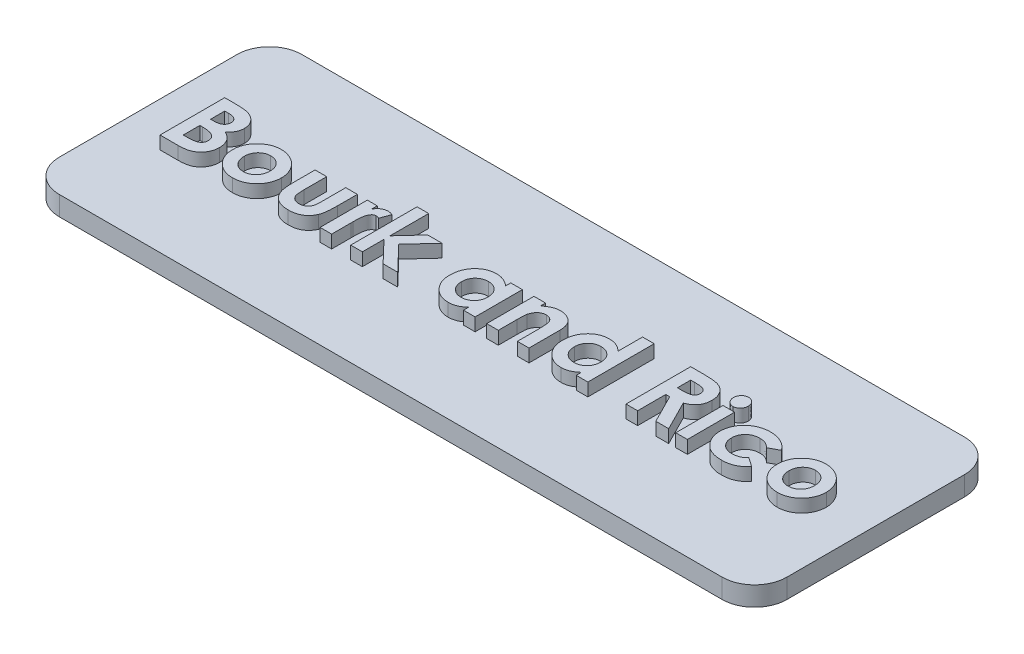
SolidWorks part; units mm, degrees
ref_plane "Front Plane" through (0, 0, 0) normal (0, 0, 1) x (1, 0, 0)
ref_plane "Top Plane" through (0, 0, 0) normal (0, 1, 0) x (1, 0, 0)
ref_plane "Right Plane" through (0, 0, 0) normal (1, 0, 0) x (0, 0, -1)
sketch "Sketch1" plane through (0, 0, 0) normal (0, 1, 0) x (1, 0, 0)
  line L1 (0, 7.5) -> (45, 7.5)
  line L2 (0, 7.5) -> (0, -7.5)
  line L3 (0, -7.5) -> (45, -7.5)
  line L4 (45, 7.5) -> (45, -7.5)
  line L5 (0, 7.5) -> (45, -7.5) construction
  line L6 (0, -7.5) -> (45, 7.5) construction
  dimension "D1" = 15
  dimension "D2" = 45
  dimension "D3" = 0
extrude "Boss-Extrude1" add sketch "Sketch1" along normal blind 1.2
sketch "Sketch2" plane through (0, 1.2, 0) normal (0, 1, 0) x (1, 0, 0)
  line L0 (0, -2) -> (45, -2) construction
  line L3 (0, -7.5) -> (45, -7.5) construction
  text T1 "<b>Bourk and Rico</b>" font "Century Gothic" height 4
  dimension "D1" = 5.5
extrude "Boss-Extrude2" add sketch "Sketch2" along normal blind 0.8
fillet "Fillet1" radius 2 4 edges at (45, 0.6, -7.5) (45, 0.6, 7.5) (0, 0.6, 7.5) (0, 0.6, -7.5)
